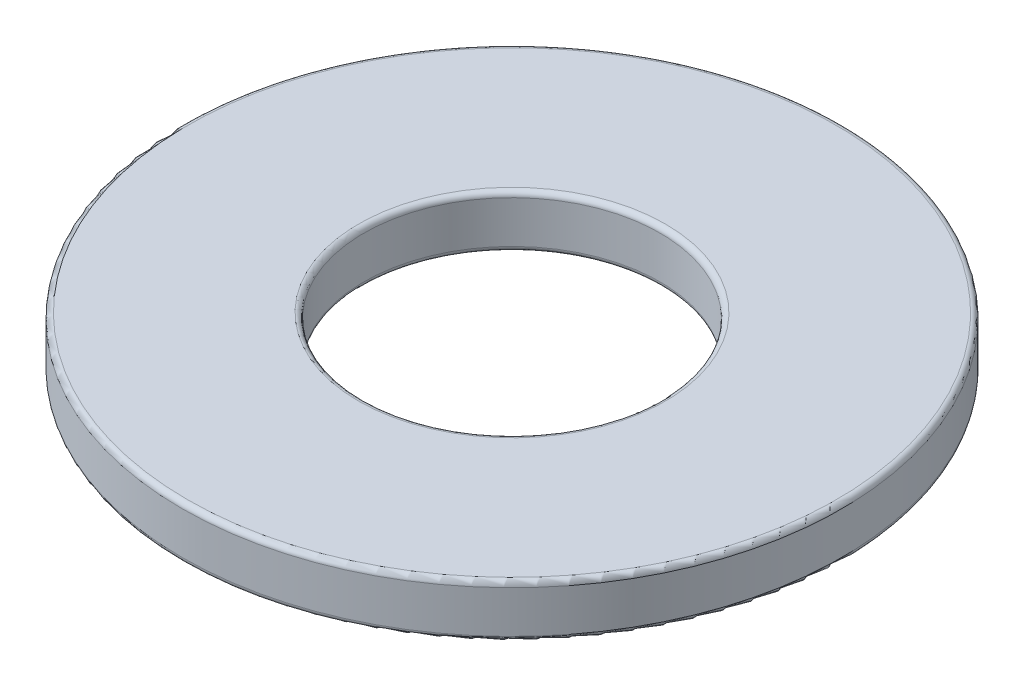
SolidWorks part; units mm, degrees
ref_plane "Front Plane" through (0, 0, 0) normal (0, 0, 1) x (1, 0, 0)
ref_plane "Top Plane" through (0, 0, 0) normal (0, 1, 0) x (1, 0, 0)
ref_plane "Right Plane" through (0, 0, 0) normal (1, 0, 0) x (0, 0, -1)
sketch "Sketch1" plane through (0, 0, 0) normal (0, 1, 0) x (1, 0, 0)
  circle A0 centre (0, 0) radius 7.9375
  circle A1 centre (0, 0) radius 3.5687
  dimension "D1" = 7.1374
  dimension "D2" = 15.875
extrude "Boss-Extrude1" add sketch "Sketch1" along normal blind 1.27
fillet "Fillet1" radius 0.127 4 edges at (0, 0, 3.5687) (0, 0, 7.9375) (0, 1.27, 3.5687) (0, 1.27, 7.9375)
